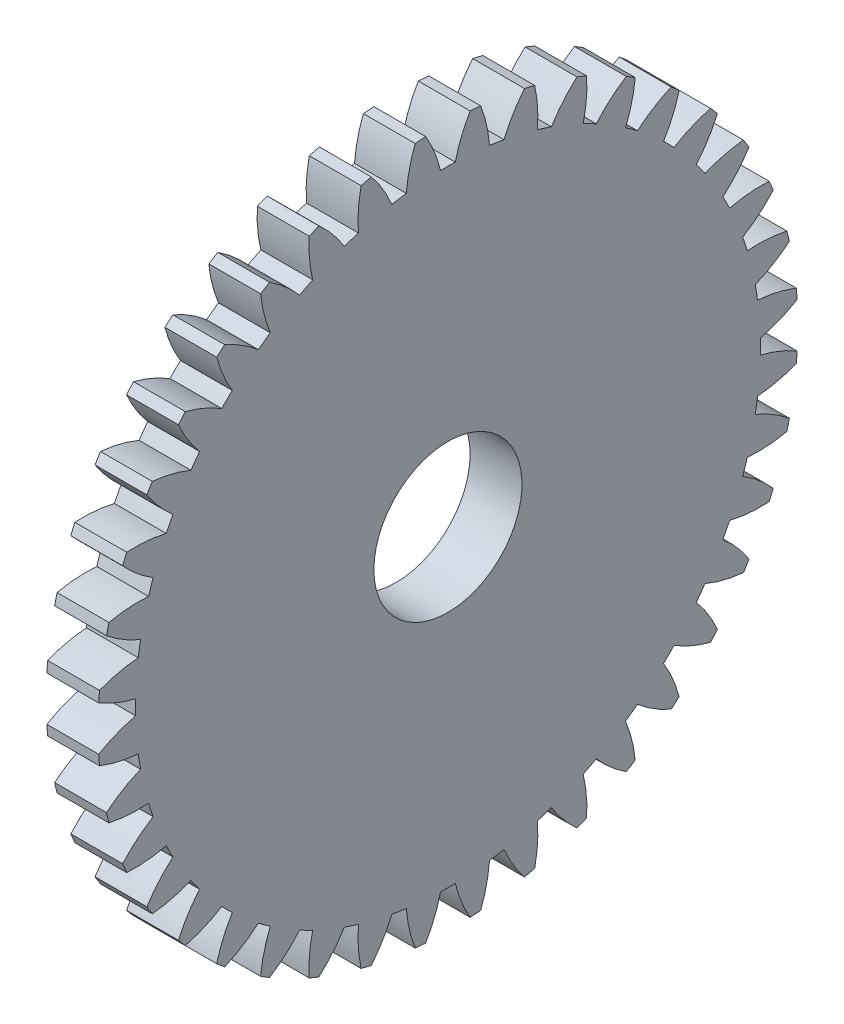
SolidWorks part; units mm, degrees
ref_plane "Plane1" through (0, 0, 0) normal (0, 0, 1) x (1, 0, 0)
ref_plane "Plane2" through (0, 0, 0) normal (0, 1, 0) x (1, 0, 0)
ref_plane "Plane3" through (0, 0, 0) normal (1, 0, 0) x (0, 0, -1)
other "Configuration Table"
sketch "HoldingSke" plane through (0, 0, 0) normal (0, 1, 0) x (1, 0, 0)
  line L0 (0, 0) -> (0.3405, -0.2857)
  line L1 (-15, 0) -> (100, 0) construction
  line L2 (0, 0) -> (-2.1039, 2.3779)
  line L3 (0, 0) -> (-11.863, 4.5341)
  line L4 (0, 0) -> (6.6156, 5.5511)
  line L5 (0, 0) -> (-46.8476, -17.4728)
  line L6 (0, 0) -> (-5.8027, -3.9151)
  line L7 (-2.1039, 2.3779) -> (8.6586, 51.2059)
  line L8 (-76.2, 54.61) -> (-73.4, 54.61)
  line L9 (-71.009, 38.7566) -> (-53.1078, 45.2721)
  line L10 (-76.2, 71.12) -> (104.1128, 71.12)
  line L11 (0, 0) -> (-7, 0)
  line L12 (-76.2, 101.6) -> (-76.123, 101.6)
  line L13 (24.9733, 27.94) -> (52.9518, 28.4284)
  line L14 (24.9733, 27.94) -> (24.9743, 27.94)
  line L15 (24.9733, 27.94) -> (100.4006, 29.5858)
  line L16 (-63.627, -2.25) -> (-12.827, -2.25)
  circle A0 centre (0, 0) radius 10
  circle A1 centre (0, 0) radius 37.5
  circle A2 centre (0, 0) radius 37.5
  circle A3 centre (0, 0) radius 10
  dimension "MHD" = 75
  dimension "Hub_dia" = 75
  dimension "Bore" = 20
  dimension "MBD" = 20
  dimension "Num_teeth" = 40
  dimension "Pitch" = 0.4444
  dimension "Overall_len" = 50
  dimension "Show_teeth" = 40
  dimension "Thickness" = 7
  dimension "OAL" = 50.0001
  dimension "T_dim" = 2.8
  dimension "Ap" = 20
  dimension "H" = 19.05
  dimension "Pitch_radius" = 180.3128
  dimension "Width" = 7
  dimension "Backlash" = 0.077
  dimension "Addendum_fac" = 1
  dimension "Dedendum_fac" = 1.25
  dimension "Clearance_fac" = 0.25
  dimension "Dedendum_add" = 0.001
  dimension "Module" = 2.25
sketch "BasProSke" plane through (0, 0, 0) normal (0, 1, 0) x (1, 0, 0)
  line L0 (-10, 0) -> (60, 0) construction
  line L1 (0, 0) -> (0, 47.25)
  line L2 (0, 0) -> (7, 0)
  line L3 (7, 0) -> (7, 47.25)
  line L4 (7, 47.25) -> (0, 47.25)
  dimension "Thickness" = 7
  dimension "Diameter" = 94.5
revolve "Base-Revolve" add sketch "BasProSke" angle 360 about L0
sketch "TooCutSke" plane through (0, 0, 0) normal (1, 0, 0) x (0, 0, -1)
  line L1 (0, 0) -> (0, 107) construction
  line L2 (0, 0) -> (-1.9014, 44.9598) construction
  line L3 (0, 0) -> (-7.0567, 89.6635) construction
  line L4 (-1.9014, 44.9598) -> (-3.5283, 44.8318) construction
  arc A0 (0.9959, 42.1747) -> (-0.9959, 42.1747) centre (0, 0) ccw
  arc A1 (3.0144, 47.1792) -> (-3.0144, 47.1792) centre (0, 0) ccw
  circle A2 centre (0, 0) radius 45 construction
  circle A3 centre (0, 0) radius 42.2862 construction
  arc A4 (-0.9959, 42.1747) -> (-3.0144, 47.1792) centre (-18.5098, 38.0198) ccw
  arc A5 (3.0144, 47.1792) -> (0.9959, 42.1747) centre (18.5098, 38.0198) ccw
  dimension "Root_dia" = 84.373
  dimension "Overcut_dia" = 94.5508
  dimension "Pitch_dia" = 90
  dimension "Base_dia" = 84.5723
  dimension "Flank_rad" = 18
  dimension "Half_ang" = 4.5
  dimension "Half_CT" = 1.6319
extrude "ToothCut" cut sketch "TooCutSke" along normal through all
fillet "Breaks" [suppressed] radius 0.045
fillet "RootFillets" [suppressed] radius 0.5635
pattern_circular "TeethCuts" count 40 every 9 about axis through (-10, 0, 0) along (1, 0, 0) of "ToothCut", "RootFillets", "Breaks"
sketch "HubNeaOneSke" plane through (0, 0, 0) normal (-1, 0, 0) x (0, 0, 1)
  circle A0 centre (0, 0) radius 37.5
  dimension "Diameter" = 75
extrude "HubNearOne" [suppressed] add sketch "HubNeaOneSke" along normal blind 43.0001
sketch "HubNeaBotSke" plane through (0, 0, 0) normal (-1, 0, 0) x (0, 0, 1)
  circle A0 centre (0, 0) radius 37.5
  dimension "Diameter" = 75
extrude "HubNearBoth" [suppressed] add sketch "HubNeaBotSke" along normal blind 21.5
ref_plane "FarPln" through (7, 0, 0) normal (1, 0, 0) x (0, 0, -1)
sketch "HubFarSke" plane through (7, 0, 0) normal (1, 0, 0) x (0, 0, -1)
  circle A0 centre (0, 0) radius 37.5
  dimension "Diameter" = 75
extrude "HubFar" [suppressed] add sketch "HubFarSke" along normal blind 21.5
sketch "BorSke" plane through (0, 0, 0) normal (1, 0, 0) x (0, 0, -1)
  circle A0 centre (0, 0) radius 10
  dimension "Diameter" = 20
extrude "Bore" cut sketch "BorSke" along normal mid plane 100.0001
sketch "KeySke" plane through (0, 0, 0) normal (1, 0, 0) x (0, 0, -1)
  line L0 (-3, 0) -> (-3, 12.8)
  line L1 (-3, 12.8) -> (3, 12.8)
  line L2 (3, 12.8) -> (3, 0)
  line L3 (0, 0) -> (0, 34) construction
  line L4 (-3, 0) -> (3, 0)
  dimension "Offset" = 12.8
  dimension "Width" = 6
extrude "Keyway" [suppressed] cut sketch "KeySke" along normal mid plane 100.0001
pattern_circular "Keyway2" [suppressed] count 2 every 90 about axis through (-10, 0, 0) along (1, 0, 0)
equation "' \"Module@HoldingSke\" = 6.35"
equation "' \"Num_teeth@HoldingSke\" = 12"
equation "' \"Ap@HoldingSke\" =  20"
equation "' \"Ap@HoldingSke\" = 20"
equation "' \"Width@HoldingSke\" = 0.5 * 25.4"
equation "' \"Hub_dia@HoldingSke\"= 1 * 25.4"
equation "' \"Hub_dia@HoldingSke\" = 1 * 25.4"
equation "' \"Overall_len@HoldingSke\" = 1.0 * 25.4"
equation "' \"Bore@HoldingSke\" = 0.75 * 25.4"
equation "' \"T_dim@HoldingSke\" = 0.1 * 25.4"
equation "' \"Width@KeySke\" = 0.25 * 25.4"
equation "' \"Show_teeth@HoldingSke\" = 13"
equation "' \"Backlash@HoldingSke\" = 0.009 * 25.4"
equation "' \"Addendum_fac@HoldingSke\" = 1.0"
equation "' \"Dedendum_fac@HoldingSke\" = 1.25"
equation "' \"Dedendum_add@HoldingSke\" = 0.00005 * 25.4"
equation "' \"Clearance_fac@HoldingSke\" = 0.25"
equation "\"Pitch@HoldingSke\" = 1 / \"Module@HoldingSke\""
equation "\"Overcut_dia@TooCutSke\" = (\"Num_teeth@HoldingSke\" + 2 * \"Addendum_fac@HoldingSke\") / \"Pitch@HoldingSke\" + 0.002 * 25.4"
equation "\"Pitch_dia@TooCutSke\" = \"Num_teeth@HoldingSke\" / \"Pitch@HoldingSke\""
equation "\"Base_dia@TooCutSke\" = \"Num_teeth@HoldingSke\" / \"Pitch@HoldingSke\" * cos((\"Ap@HoldingSke\"  * 3.14159265 / 180))"
equation "\"Root_dia@TooCutSke\" = (\"Num_teeth@HoldingSke\" + 2) / \"Pitch@HoldingSke\" - 2 * (\"Addendum_fac@HoldingSke\" + \"Dedendum_fac@HoldingSke\") / \"Pitch@HoldingSke\" - \"Dedendum_add@HoldingSke\" * 2"
equation "\"Half_ang@TooCutSke\" = 180 / \"Num_teeth@HoldingSke\""
equation "\"Half_CT@TooCutSke\" = \"Num_teeth@HoldingSke\" / \"Pitch@HoldingSke\" * sin((3.14159265 / 2 / \"Num_teeth@HoldingSke\")) / 2 - 7 * \"Backlash@HoldingSke\" / 4"
equation "\"Flank_rad@TooCutSke\" = \"Num_teeth@HoldingSke\" / \"Pitch@HoldingSke\" / 5"
equation "\"Radius@RootFillets\" = \"Clearance_fac@HoldingSke\" / \"Pitch@HoldingSke\" + \"Dedendum_add@HoldingSke\""
equation "\"Break_rad@Breaks\" = 0.02 / \"Pitch@HoldingSke\""
equation "\"Thickness@HoldingSke\" = \"Width@HoldingSke\""
equation "\"OAL@HoldingSke\" = \"Thickness@HoldingSke\""
equation "\"MHD@HoldingSke\" = (\"Num_teeth@HoldingSke\" + 2) / \"Pitch@HoldingSke\" - 2 * (\"Addendum_fac@HoldingSke\" + \"Dedendum_fac@HoldingSke\")  / \"Pitch@HoldingSke\" - \"Dedendum_add@HoldingSke\" * 2"
equation "\"MBD@HoldingSke\" = (\"Num_teeth@HoldingSke\" + 2) / \"Pitch@HoldingSke\" - 2 * (\"Addendum_fac@HoldingSke\" + \"Dedendum_fac@HoldingSke\")  / \"Pitch@HoldingSke\" - \"Dedendum_add@HoldingSke\" * 2 - 0.002 * 25.4"
equation "\"MHD@HoldingSke\" = ((sgn( \"MHD@HoldingSke\" - \"Hub_dia@HoldingSke\" )-1)*( \"MHD@HoldingSke\" - \"Hub_dia@HoldingSke\" ))/-2+ \"Hub_dia@HoldingSke\""
equation "\"MBD@HoldingSke\" = ((sgn( \"MBD@HoldingSke\" - \"Bore@HoldingSke\" )-1)*( \"MBD@HoldingSke\" - \"Bore@HoldingSke\" ))/-2+ \"Bore@HoldingSke\""
equation "\"OAL@HoldingSke\" = ((sgn( \"OAL@HoldingSke\" - \"Overall_len@HoldingSke\" )+1)*( \"OAL@HoldingSke\" - \"Overall_len@HoldingSke\" ))/2 + \"Overall_len@HoldingSke\" + 0.000002 * 25.4"
equation "\"Num_teeth@TeethCuts\" = int( \"Show_teeth@HoldingSke\" ) + 1"
equation "\"Num_teeth@TeethCuts\" = ((sgn( \"Num_teeth@TeethCuts\" - \"Num_teeth@HoldingSke\" )-1)*( \"Num_teeth@TeethCuts\" - \"Num_teeth@HoldingSke\" ))/-2+ \"Num_teeth@HoldingSke\""
equation "\"Num_teeth@TeethCuts\" = ((sgn( \"Num_teeth@TeethCuts\" - 2.0)+1)*( \"Num_teeth@TeethCuts\" - 2.0))/2 +2.0"
equation "\"Angle@TeethCuts\" = 360.0 / \"Num_teeth@HoldingSke\""
equation "\"Diameter@BasProSke\" = (\"Num_teeth@HoldingSke\" + 2 * \"Addendum_fac@HoldingSke\") / \"Pitch@HoldingSke\""
equation "\"Thickness@BasProSke\"  = \"Thickness@HoldingSke\""
equation "' \"Fillet_rad@BasProSke\" =  \"Thickness@HoldingSke\" * 0.05"
equation "' \"Fillet_rad@BasProSke\" = \"Thickness@HoldingSke\" * 0.05"
equation "\"MHD@HoldingSke\" = ((sgn( \"MHD@HoldingSke\" - \"Root_dia@TooCutSke\" )-1)*( \"MHD@HoldingSke\" - \"Root_dia@TooCutSke\" ))/-2+ \"Root_dia@TooCutSke\""
equation "\"Diameter@HubNeaOneSke\" = \"MHD@HoldingSke\""
equation "\"Length@HubNearOne\" = \"OAL@HoldingSke\" - \"Thickness@BasProSke\""
equation "\"Diameter@HubNeaBotSke\" = \"MHD@HoldingSke\""
equation "\"Length@HubNearBoth\" = ( \"OAL@HoldingSke\" - \"Thickness@BasProSke\" ) / 2.0"
equation "\"Thickness@FarPln\" = \"Thickness@BasProSke\""
equation "\"Diameter@HubFarSke\" = \"MHD@HoldingSke\""
equation "\"Length@HubFar\" = ( \"OAL@HoldingSke\" - \"Thickness@BasProSke\" ) / 2.0"
equation "\"Diameter@BorSke\" = \"MBD@HoldingSke\""
equation "\"D1@Bore\" = \"OAL@HoldingSke\" * 2.0"
equation "\"D1@Keyway\" = \"OAL@HoldingSke\" * 2.0"
equation "\"Offset@KeySke\" = \"T_dim@HoldingSke\" + \"MBD@HoldingSke\" / 2.0"
